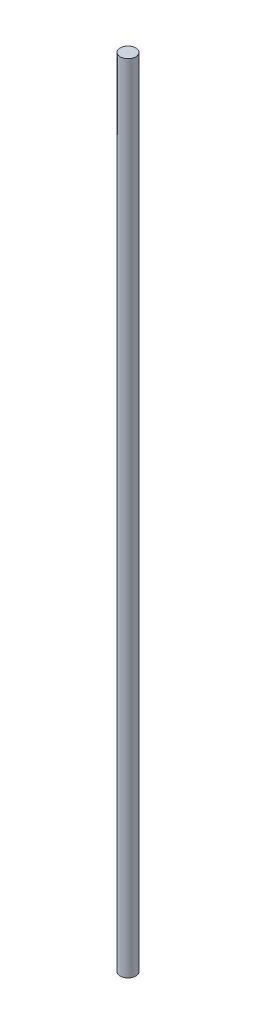
SolidWorks part; units mm, degrees
material "Chrome Stainless Steel"
ref_plane "Front Plane" through (0, 0, 0) normal (0, 0, 1) x (1, 0, 0)
ref_plane "Top Plane" through (0, 0, 0) normal (0, 1, 0) x (1, 0, 0)
ref_plane "Right Plane" through (0, 0, 0) normal (1, 0, 0) x (0, 0, -1)
sketch "Sketch1" plane through (0, 0, 0) normal (0, 1, 0) x (1, 0, 0)
  circle A0 centre (0, 0) radius 4
  dimension "D1" = 8
extrude "Boss-Extrude1" add sketch "Sketch1" along normal blind 410
